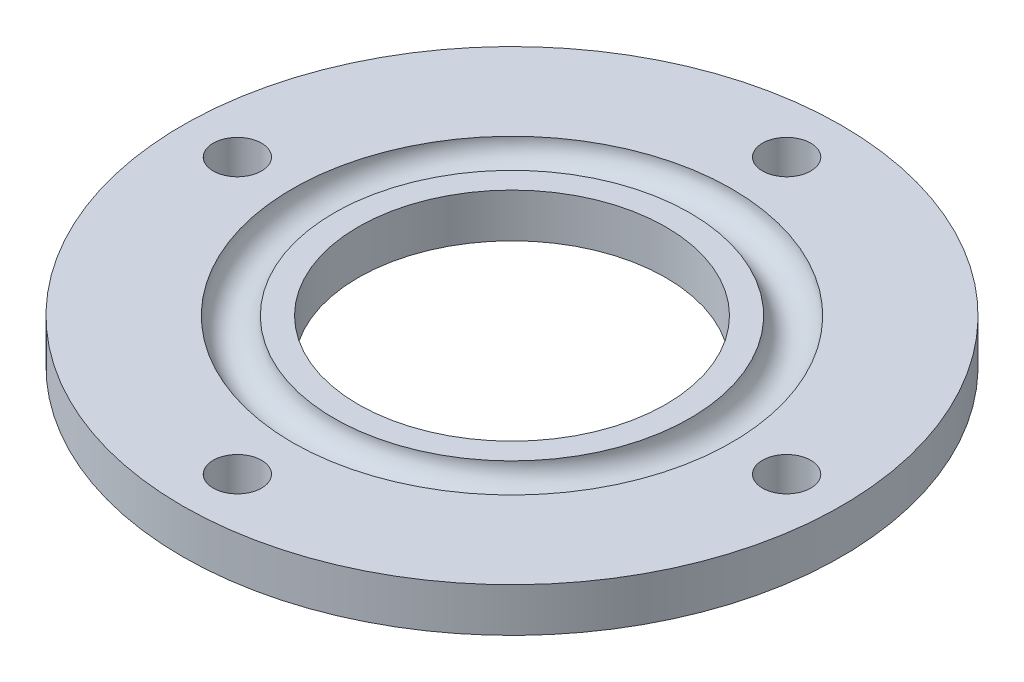
SolidWorks part; units mm, degrees
ref_plane "前视基准面" through (0, 0, 0) normal (0, 0, 1) x (1, 0, 0)
ref_plane "上视基准面" through (0, 0, 0) normal (0, 1, 0) x (1, 0, 0)
ref_plane "右视基准面" through (0, 0, 0) normal (1, 0, 0) x (0, 0, -1)
sketch "草图1" plane through (0, 0, 0) normal (0, 1, 0) x (1, 0, 0)
  circle A0 centre (0, 0) radius 15
  circle A1 centre (0, 0) radius 7
  dimension "D1" = 30
  dimension "D2" = 14
extrude "凸台-拉伸1" add sketch "草图1" along normal blind 2
sketch "草图2" plane through (0, 2, 0) normal (0, 1, 0) x (1, 0, 0)
  line L0 (-15, 0) -> (15, 0) construction
  line L1 (0, 15) -> (0, -15) construction
  circle A0 centre (0, 0) radius 15 construction
  circle A1 centre (12.5, 0) radius 1.1
  circle A2 centre (0, -12.5) radius 1.1
  circle A3 centre (-12.5, 0) radius 1.1
  circle A4 centre (0, 12.5) radius 1.1
  point P19 (0, 0)
  dimension "D1" = 12.5
  dimension "D2" = 2.2
  dimension "D3" = 4
extrude "切除-拉伸1" cut sketch "草图2" against normal up to next
sketch "草图3" plane through (0, 0, 0) normal (0, 0, 1) x (1, 0, 0)
  line L0 (-15, 2) -> (15, 2) construction
  line L1 (0, 2) -> (0, 13.3294) construction
  circle A0 centre (9.05, 2) radius 0.95
  dimension "D2" = 1.9
  dimension "D1" = 9.05
revolve "切除-旋转1" cut sketch "草图3" angle 360 about L1
